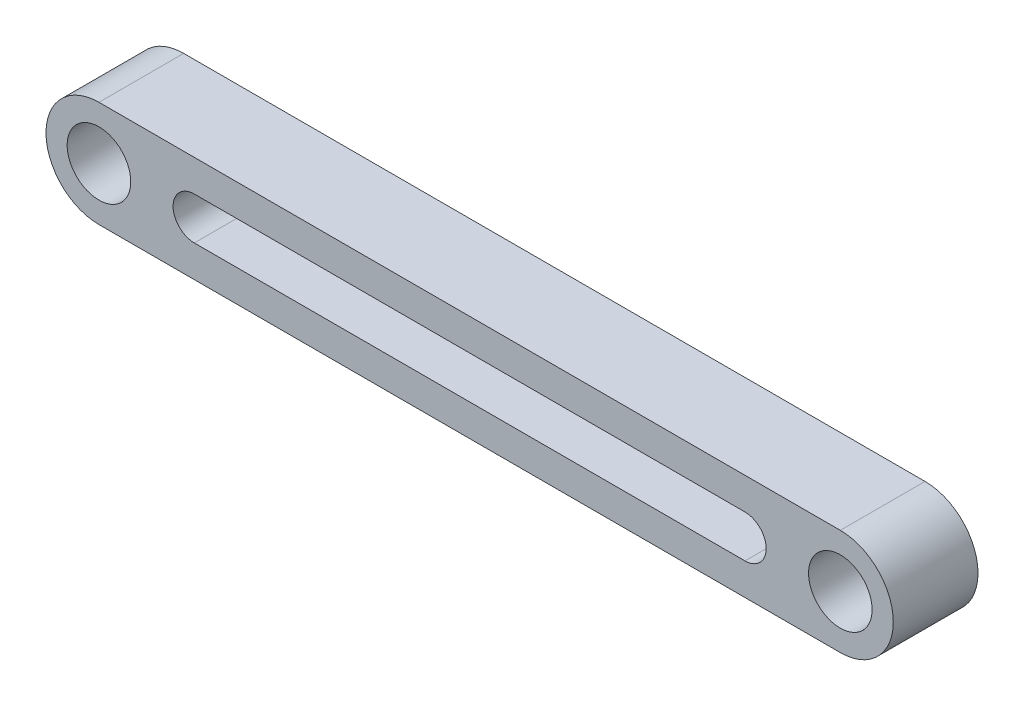
SolidWorks part; units mm, degrees
ref_plane "Plan de face" through (0, 0, 0) normal (0, 0, 1) x (1, 0, 0)
ref_plane "Plan de dessus" through (0, 0, 0) normal (0, 1, 0) x (1, 0, 0)
ref_plane "Plan de droite" through (0, 0, 0) normal (1, 0, 0) x (0, 0, -1)
sketch "Esquisse1" plane through (0, 0, 0) normal (0, 0, 1) x (1, 0, 0)
  line L0 (0, 0) -> (35, 0) construction
  line L1 (0, 2.5) -> (35, 2.5)
  line L2 (0, -2.5) -> (35, -2.5)
  line L3 (4.5, 0) -> (30.5, 0) construction
  line L4 (4.5, 1) -> (30.5, 1)
  line L5 (4.5, -1) -> (30.5, -1)
  arc A0 (0, 2.5) -> (0, -2.5) centre (0, 0) ccw
  arc A1 (35, -2.5) -> (35, 2.5) centre (35, 0) ccw
  circle A2 centre (0, 0) radius 1.5
  circle A3 centre (35, 0) radius 1.5
  arc A4 (4.5, 1) -> (4.5, -1) centre (4.5, 0) ccw
  arc A5 (30.5, -1) -> (30.5, 1) centre (30.5, 0) ccw
  point P3 (17.5, 0)
  point P14 (17.5, 0)
  point P19 (3.5, 0)
  point P23 (1.5, 0)
  dimension "D1" = 3
  dimension "D3" = 35
  dimension "D2" = 5
  dimension "D4" = 2
  dimension "D5" = 2
extrude "Boss.-Extru.1" add sketch "Esquisse1" along normal blind 4
